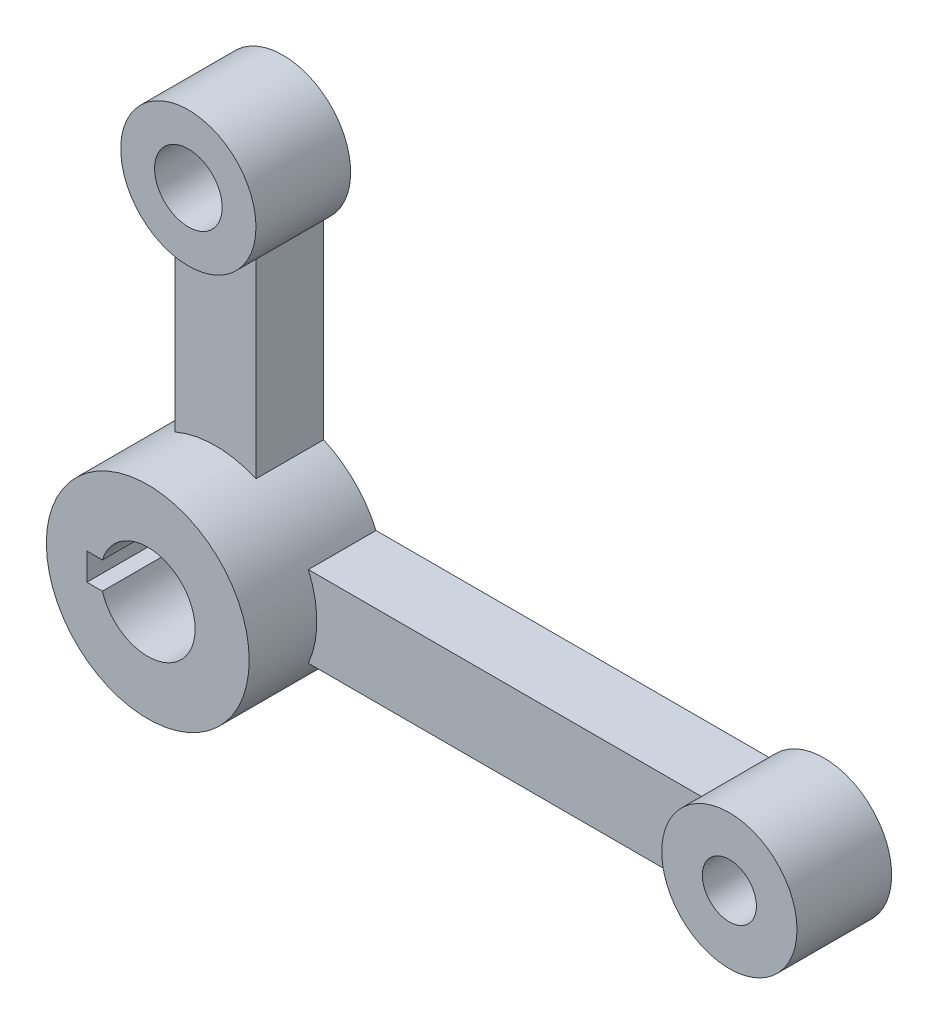
SolidWorks part; units mm, degrees
ref_plane "前视基准面" through (0, 0, 0) normal (0, 0, 1) x (1, 0, 0)
ref_plane "上视基准面" through (0, 0, 0) normal (0, 1, 0) x (1, 0, 0)
ref_plane "右视基准面" through (0, 0, 0) normal (1, 0, 0) x (0, 0, -1)
ref_plane "基准面1" through (0, 0, -10) normal (0, 0, 1) x (1, 0, 0)
sketch "草图1" plane through (0, 0, -10) normal (0, 0, 1) x (1, 0, 0)
  circle A0 centre (0, 0) radius 15
extrude "凸台-拉伸1" add sketch "草图1" along normal blind 20
ref_plane "基准面2" through (0, 0, -5) normal (0, 0, 1) x (1, 0, 0)
sketch "草图10" plane through (0, 0, -10) normal (0, 0, 1) x (1, 0, 0)
  circle A0 centre (0, 50) radius 10
extrude "凸台-拉伸10" add sketch "草图10" along normal blind 14
sketch "草图11" plane through (0, 0, -10) normal (0, 0, 1) x (1, 0, 0)
  circle A0 centre (80, 0) radius 10
extrude "凸台-拉伸11" add sketch "草图11" along normal blind 14
sketch "草图12" plane through (0, 0, -10) normal (0, 0, 1) x (1, 0, 0)
  line L0 (-6, 0) -> (6, 0)
  line L1 (6, 0) -> (6, 50)
  line L2 (6, 50) -> (-6, 50)
  line L3 (-6, 50) -> (-6, 0)
extrude "凸台-拉伸12" add sketch "草图12" along normal blind 10
sketch "草图13" plane through (0, 0, -10) normal (0, 0, 1) x (1, 0, 0)
  line L0 (0, -6) -> (80, -6)
  line L1 (80, -6) -> (80, 6)
  line L2 (80, 6) -> (0, 6)
  line L3 (0, 6) -> (0, -6)
extrude "凸台-拉伸13" add sketch "草图13" along normal blind 10
sketch "草图14" plane through (0, 0, -10) normal (0, 0, 1) x (1, 0, 0)
  circle A0 centre (0, 50) radius 5
extrude "切除-拉伸1" cut sketch "草图14" along normal through all
sketch "草图15" plane through (0, 0, -10) normal (0, 0, 1) x (1, 0, 0)
  circle A0 centre (80, 0) radius 4
extrude "切除-拉伸2" cut sketch "草图15" along normal through all
sketch "草图16" plane through (0, 0, -10) normal (0, 0, 1) x (1, 0, 0)
  circle A0 centre (0, 0) radius 7
extrude "切除-拉伸3" cut sketch "草图16" along normal through all
sketch "草图17" plane through (0, 0, -10) normal (0, 0, 1) x (1, 0, 0)
  line L0 (-9, -2) -> (-6, -2)
  line L1 (-6, -2) -> (-6, 2)
  line L2 (-6, 2) -> (-9, 2)
  line L3 (-9, 2) -> (-9, -2)
extrude "切除-拉伸4" cut sketch "草图17" along normal through all
